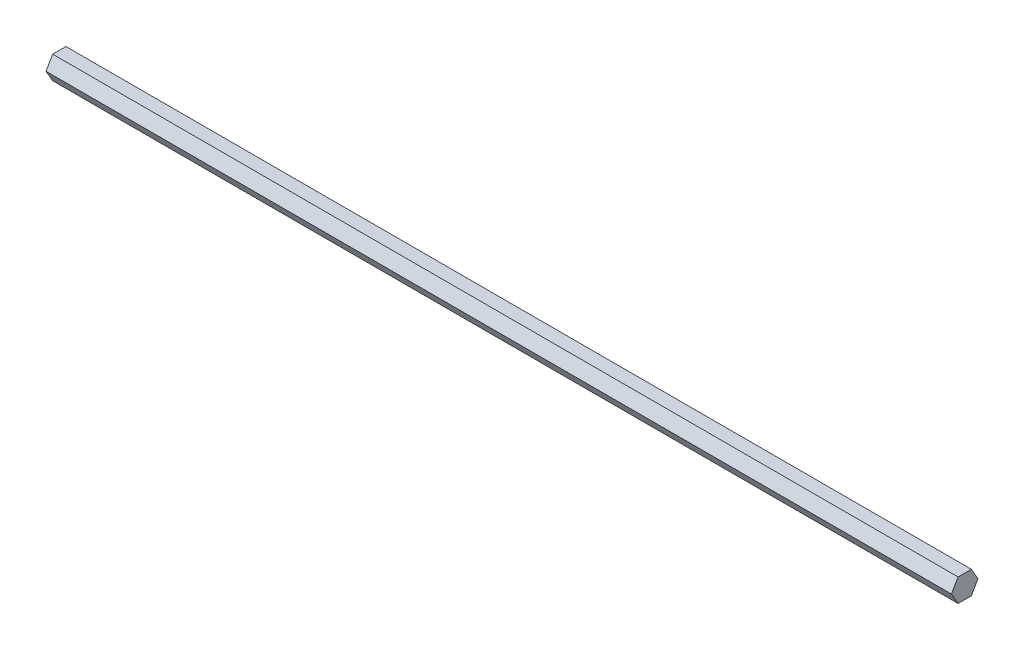
SolidWorks part; units mm, degrees
ref_plane "Alzado" through (0, 0, 0) normal (0, 0, 1) x (1, 0, 0)
ref_plane "Planta" through (0, 0, 0) normal (0, 1, 0) x (1, 0, 0)
ref_plane "Vista lateral" through (0, 0, 0) normal (1, 0, 0) x (0, 0, -1)
sketch "Croquis1" plane through (0, 0, 0) normal (1, 0, 0) x (0, 0, -1)
  line L1 (7.3323, 0) -> (3.6662, 6.35)
  line L2 (3.6662, 6.35) -> (-3.6662, 6.35)
  line L3 (-3.6662, 6.35) -> (-7.3323, 0)
  line L4 (-7.3323, 0) -> (-3.6662, -6.35)
  line L5 (-3.6662, -6.35) -> (3.6662, -6.35)
  line L6 (3.6662, -6.35) -> (7.3323, 0)
  circle A0 centre (0, 0) radius 6.35 construction
  dimension "D1" = 12.7
extrude "Saliente-Extruir1" add sketch "Croquis1" along normal blind 500
